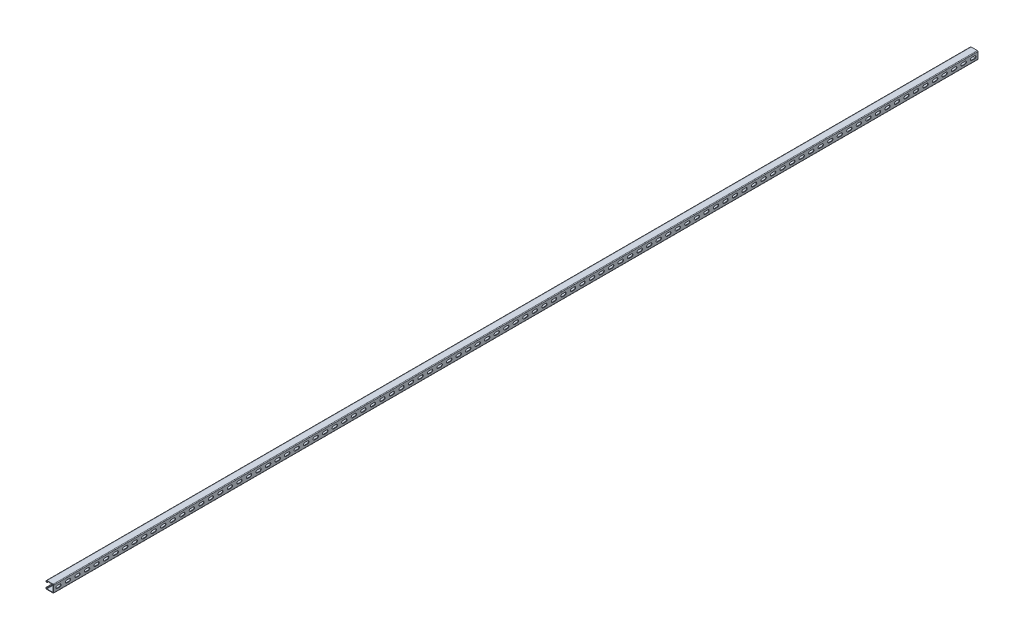
SolidWorks part; units mm, degrees
ref_plane "Front Plane" through (0, 0, 0) normal (0, 0, 1) x (1, 0, 0)
ref_plane "Top Plane" through (0, 0, 0) normal (0, 1, 0) x (1, 0, 0)
ref_plane "Right Plane" through (0, 0, 0) normal (1, 0, 0) x (0, 0, -1)
sketch "Sketch1" plane through (0, 0, 0) normal (0, 0, 1) x (1, 0, 0)
  line L0 (0, 0) -> (-41.275, 0) construction
  line L3 (-41.275, 20.6375) -> (0, 20.6375) construction
  line L4 (-41.275, 20.6375) -> (-41.275, -20.6375) construction
  line L5 (-41.275, -20.6375) -> (0, -20.6375) construction
  line L6 (0, 20.6375) -> (0, -20.6375) construction
  line L7 (-36.2267, 20.6375) -> (-3.4607, 20.6375)
  line L8 (0, 17.1767) -> (0, -17.1767)
  line L9 (-2.794, -17.1767) -> (-2.794, 17.1767)
  line L10 (-3.4608, 17.8435) -> (-36.2267, 17.8435)
  line L11 (-41.275, 15.5892) -> (-41.275, 14.5732)
  line L12 (-37.8142, 11.1125) -> (-35.5346, 11.1125)
  line L14 (-35.5346, 13.9065) -> (-37.8142, 13.9065)
  line L15 (-38.481, 14.5732) -> (-38.481, 15.5892)
  line L16 (-38.481, -14.5733) -> (-38.481, -15.5893)
  line L17 (-35.5346, -13.9065) -> (-37.8142, -13.9065)
  line L18 (-37.8142, -11.1125) -> (-35.5346, -11.1125)
  line L19 (-41.275, -15.5893) -> (-41.275, -14.5733)
  line L20 (-3.4607, -17.8435) -> (-36.2267, -17.8435)
  line L21 (-36.2267, -20.6375) -> (-3.4607, -20.6375)
  line L22 (-2.794, -20.6375) -> (-2.794, 20.6375) construction
  arc A1 (0, 17.1767) -> (-3.4607, 20.6375) centre (-3.4607, 17.1767) ccw
  arc A2 (-2.794, 17.1767) -> (-3.4608, 17.8435) centre (-3.4607, 17.1767) ccw
  arc A4 (-36.2267, 20.6375) -> (-41.275, 15.5892) centre (-36.2267, 15.5892) ccw
  arc A5 (-41.275, 14.5732) -> (-37.8142, 11.1125) centre (-37.8142, 14.5732) ccw
  arc A6 (-35.5346, 11.1125) -> (-35.5346, 13.9065) centre (-35.5346, 12.5095) ccw
  arc A7 (-37.8142, 13.9065) -> (-38.481, 14.5732) centre (-37.8142, 14.5732) cw
  arc A8 (-38.481, 15.5892) -> (-36.2267, 17.8435) centre (-36.2267, 15.5892) cw
  arc A9 (-38.481, -15.5893) -> (-36.2267, -17.8435) centre (-36.2267, -15.5893) ccw
  arc A10 (-37.8142, -13.9065) -> (-38.481, -14.5733) centre (-37.8142, -14.5733) ccw
  arc A11 (-35.5346, -11.1125) -> (-35.5346, -13.9065) centre (-35.5346, -12.5095) cw
  arc A12 (-41.275, -14.5733) -> (-37.8142, -11.1125) centre (-37.8142, -14.5733) cw
  arc A13 (-36.2267, -20.6375) -> (-41.275, -15.5893) centre (-36.2267, -15.5893) cw
  arc A14 (-2.794, -17.1767) -> (-3.4607, -17.8435) centre (-3.4607, -17.1767) cw
  arc A15 (0, -17.1767) -> (-3.4607, -20.6375) centre (-3.4607, -17.1767) cw
  point P24 (0, 20.6375)
  point P65 (-2.794, 0)
  dimension "D1" = 3.4608
  dimension "D2" = 5.0482
  dimension "D3" = 3.4608
  dimension "Ht." = 41.275
  dimension "Wd." = 41.275
  dimension "Thk." = 2.794
  dimension "D4" = 9.525
  dimension "D5" = 7.1374
extrude "Boss-Extrude1" add sketch "Sketch1" against normal blind 4927.6
sketch "Sketch3" plane through (0, 0, 0) normal (1, 0, 0) x (0, 0, -1)
  line L0 (0, 0) -> (4927.6, 0) construction
  point P2 (101.6, 0)
  point P3 (4826, 0)
  dimension "D1" = 101.6
  dimension "D2" = 101.6
  dimension "D3" = 4927.6
sketch "Sketch2" plane through (0, 0, 0) normal (1, 0, 0) x (0, 0, -1)
  line L0 (18.2562, 0) -> (32.5437, 0) construction
  line L1 (18.2562, 7.1438) -> (32.5437, 7.1438)
  line L2 (18.2562, -7.1438) -> (32.5437, -7.1438)
  line L3 (18.2562, 0) -> (0, 0) construction
  line L4 (25.4, 0) -> (76.2, 0) construction
  line L5 (0, -17.1767) -> (0, 17.1767) construction
  arc A0 (18.2562, 7.1438) -> (18.2562, -7.1438) centre (18.2562, 0) ccw
  arc A1 (32.5437, -7.1438) -> (32.5437, 7.1438) centre (32.5437, 0) ccw
  point P3 (25.4, 0)
  dimension "Hole to End" = 11.1125
  dimension "D2" = 25.4
extrude "Cut-Extrude1" cut sketch "Sketch2" against normal up to vertex (2.794 mm away) up to point (-2.794, 0, 0)
pattern_linear "LPattern1" count 97 spacing 50.8 along (0, 0, -1) of "Cut-Extrude1"
equation "\"D1@LPattern1\" = \"Slot Ctr.@Sketch2\""
equation "\"Hole Count@LPattern1\" = \"Lg.@Boss-Extrude1\" / \"D1@LPattern1\""
equation "\"D3@Sketch3\" = \"Lg.@Boss-Extrude1\""
